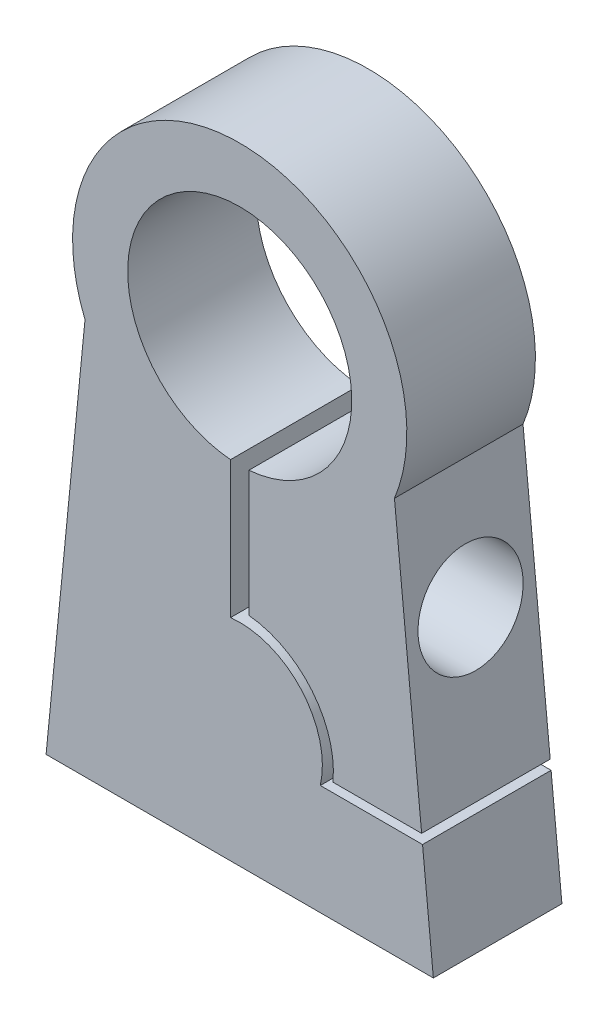
SolidWorks part; units mm, degrees
ref_plane "Front Plane" through (0, 0, 0) normal (0, 0, 1) x (1, 0, 0)
ref_plane "Top Plane" through (0, 0, 0) normal (0, 1, 0) x (1, 0, 0)
ref_plane "Right Plane" through (0, 0, 0) normal (1, 0, 0) x (0, 0, -1)
sketch "Sketch1" plane through (0, 0, 0) normal (0, 0, 1) x (1, 0, 0)
  line L0 (-13, -50) -> (13, -50)
  line L1 (-13, -50) -> (-8.4243, -3.441)
  line L2 (13, -50) -> (8.4243, -3.441)
  arc A0 (-8.4243, -3.441) -> (8.4243, -3.441) centre (0, 0) cw
  circle A1 centre (0, 0) radius 6.1
  dimension "D1" = 12.2
  dimension "D3" = 9.1
  dimension "D2" = 26
  dimension "D5" = 50
extrude "Thickness" add sketch "Sketch1" along normal mid plane 7
sketch "Sketch2" plane through (0, -50, 0) normal (0, -1, 0) x (1, 0, 0)
  line L0 (44.2539, 0) -> (-44.2539, 0) construction
  line L4 (-10.7909, 0) -> (-9.1454, -2.85)
  line L5 (-9.1454, -2.85) -> (-5.8546, -2.85)
  line L6 (-5.8546, -2.85) -> (-4.2091, 0)
  line L14 (4.2091, 0) -> (5.8546, -2.85)
  line L15 (5.8546, -2.85) -> (9.1454, -2.85)
  line L16 (9.1454, -2.85) -> (10.7909, 0)
  line L17 (0, -44.7868) -> (0, 44.7868) construction
  line L18 (4.2091, 0) -> (4.2091, 2.85)
  line L19 (4.2091, 2.85) -> (10.7909, 2.85)
  line L20 (10.7909, 2.85) -> (10.7909, 0)
  line L21 (-10.7909, 0) -> (-10.7909, 2.85)
  line L22 (-10.7909, 2.85) -> (-4.2091, 2.85)
  line L23 (-4.2091, 2.85) -> (-4.2091, 0)
  circle A0 centre (-7.5, 0) radius 2.85
  circle A1 centre (7.5, 0) radius 2.85
  dimension "D2" = 7.5
  dimension "D1" = 5.7
  dimension "D3" = 15
extrude "BotNutCut" cut sketch "Sketch2" against normal blind 2.6 from offset 2 contours A0 | A0 L22 L21 L4 | A0 L6 L23 L22 | A0 L5 L6 | A0 L4 L5 | A1 L14 L15 | A1 L15 L16 | A1 L16 L20 L19 | A1 L19 L18 L14 | A1 offset against normal yes
sketch "Sketch3" plane through (0, -50, 0) normal (0, -1, 0) x (1, 0, 0)
  line L0 (44.2539, 0) -> (-44.2539, 0) construction
  line L1 (0, -44.7868) -> (0, 44.7868) construction
  circle A0 centre (-7.5, 0) radius 1.55
  circle A1 centre (7.5, 0) radius 1.55
  dimension "D3" = 3.1
  dimension "D1" = 15
  dimension "D2" = 7.5
extrude "BotScrewCut" cut sketch "Sketch3" against normal blind 2
sketch "Sketch5" plane through (0, 0, 3.5) normal (0, 0, 1) x (1, 0, 0)
  line L0 (-0.5, -6.0795) -> (-0.5, -14)
  line L1 (-0.5, -14) -> (0.5, -14)
  line L2 (0.5, -14) -> (0.5, -6.0795)
  line L3 (0, -44.7868) -> (0, 44.7868) construction
  line L6 (55, 0) -> (-55, 0) construction
  circle A0 centre (0, 0) radius 6.1 construction
  circle A1 centre (0, -18) radius 5.1
  circle M9 centre (0, 0) radius 6.1
  dimension "D5" = 10.2
  dimension "D1" = 1
  dimension "D2" = 0.5
  dimension "D3" = 18
  dimension "D4" = 14
extrude "Cut-Extrude1" cut sketch "Sketch5" against normal up to surface (7 mm away) contours A1 L2 L0 M9
sketch "Sketch6" plane through (-0.5, 0, 0) normal (1, 0, 0) x (0, 0, -1)
  line L0 (0, 44.2539) -> (0, -44.2539) construction
  line L4 (0, -13.2909) -> (2.85, -11.6454)
  line L5 (2.85, -11.6454) -> (2.85, -8.3546)
  line L6 (2.85, -8.3546) -> (0, -6.7091)
  line L8 (0, -6.7091) -> (-2.85, -8.3546) [skipped]
  line L9 (-2.85, -8.3546) -> (-2.85, -11.6454) [skipped]
  line L10 (-2.85, -11.6454) -> (0, -13.2909) [skipped]
  line L11 (0, -6.7091) -> (-2.85, -6.7091)
  line L12 (-2.85, -6.7091) -> (-2.85, -13.2909)
  line L13 (-2.85, -13.2909) -> (0, -13.2909)
  line L14 (55, 0) -> (-55, 0) construction
  circle A0 centre (0, -10) radius 2.85 construction
  dimension "D1" = 5.7
  dimension "D2" = 10
extrude "RailNutCut" cut sketch "Sketch6" against normal blind 2.6 from offset 2 offset against normal yes
sketch "Sketch7" plane through (-0.5, 0, 0) normal (1, 0, 0) x (0, 0, -1)
  line L0 (0, 44.2539) -> (0, -44.2539) construction
  line L1 (55, 0) -> (-55, 0) construction
  circle A0 centre (0, -10) radius 1.55
  dimension "D1" = 3.1
  dimension "D2" = 10
extrude "RailScrewCut" cut sketch "Sketch7" against normal blind 2.6 and the other way up to surface other way up to face at (10.7122, -26.7205, 0)
sketch "Sketch8" plane through (0.5, 0, 0) normal (-1, 0, 0) x (0, 0, 1)
  line L0 (0, -44.2539) -> (0, 44.2539) construction
  line L1 (55, 0) -> (-55, 0) construction
  circle A0 centre (0, -10) radius 2.85
  dimension "D2" = 5.7
  dimension "D1" = 10
extrude "RailNutHeadCut" cut sketch "Sketch8" against normal up to surface (6.349 mm away) from offset 2.5 offset against normal yes
sketch "Sketch9" plane through (0, 0, 3.5) normal (0, 0, 1) x (1, 0, 0)
  line L0 (55, 0) -> (-55, 0) construction
  line L1 (4, -18.5) -> (11, -18.5)
  line L2 (4, -18.5) -> (4, -19)
  line L3 (4, -19) -> (11, -19)
  line L4 (11, -18.5) -> (11, -19)
  line L5 (0, -44.7868) -> (0, 44.7868) construction
  dimension "D1" = 18.5
  dimension "D2" = 0.5
  dimension "D3" = 7
  dimension "D4" = 4
extrude "MovementCut" cut sketch "Sketch9" against normal up to surface (7 mm away) up to face at (0, -9.001, -3.5)
sketch "Sketch10" plane through (0, 0, 0) normal (0, 0, 1) x (1, 0, 0)
  line L0 (55, 0) -> (-55, 0) construction
  line L2 (0, -44.7868) -> (0, 44.7868) construction
  line L3 (-0.5, -12.9246) -> (-0.5, -13.5279)
  line L4 (5.001, -19) -> (4.3875, -19)
  circle A0 centre (0, -18) radius 4.5
  arc A1 (-0.5, -12.9246) -> (5.001, -19) centre (0, -18) ccw
  arc A3 (-0.5, -12.9246) -> (5.001, -19) centre (0, -18) ccw construction
  dimension "D1" = 9
  dimension "D2" = 18
extrude "Boss-Extrude1" add sketch "Sketch10" along normal mid plane 7 contours L3 A1 L4 A0 | A0
sketch "Sketch11" plane through (0, 0, 0) normal (0, 1, 0) x (1, 0, 0)
  line L0 (-44.2539, 0) -> (44.2539, 0) construction
  line L1 (-20, 12.5) -> (20, 12.5)
  line L2 (-20, 12.5) -> (-20, -12.5)
  line L3 (-20, -12.5) -> (20, -12.5)
  line L4 (20, 12.5) -> (20, -12.5)
  line L5 (0, -44.7868) -> (0, 44.7868) construction
  dimension "D1" = 40
  dimension "D2" = 25
  dimension "D3" = 12.5
  dimension "D4" = 20
extrude "Cut-Extrude2" cut sketch "Sketch11" against normal up to surface (25 mm away) from offset 25
equation "\"Width\"=26"
equation "\"D2@Sketch1\"=\"Width\""
equation "\"fastenWid\"=15"
equation "\"NutDiam\"= 5.7"
equation "\"D1@Sketch3\"=\"fastenWid\""
equation "\"D2@Sketch3\"=\"fastenWid\"/2"
equation "\"ScrewDiam\"=3.1"
equation "\"D3@Sketch3\"=\"ScrewDiam\""
equation "\"ScrewDepth\"=2"
equation "\"D1@BotScrewCut\" = \"ScrewDepth\""
equation "\"D19@BotNutCut\" = \"ScrewDepth\""
equation "\"NutHeight\"=2.6"
equation "\"D1@BotNutCut\" = \"NutHeight\""
equation "\"Thick\"=7"
equation "\"D1@Thickness\" = \"Thick\""
equation "\"RailHeight\"=50"
equation "\"D5@Sketch1\"=\"RailHeight\""
equation "\"RailDiam\"=12.2"
equation "\"D1@Sketch1\"=\"RailDiam\""
equation "\"D3@Sketch1\"=\"RailDiam\"/2 +3"
equation "\"D1@Sketch7\"=\"ScrewDiam\""
equation "\"D1@Sketch2\"=\"NutDiam\""
equation "\"D2@Sketch2\"=\"fastenWid\"/2"
equation "\"D3@Sketch2\"=\"fastenWid\""
equation "\"MovementCut\"=0.5"
equation "\"D2@Sketch9\"=\"MovementCut\""
equation "\"D1@Sketch9\"=\"MovementCut\" +18"
equation "\"D1@Boss-Extrude1\"=\"Thick\""
